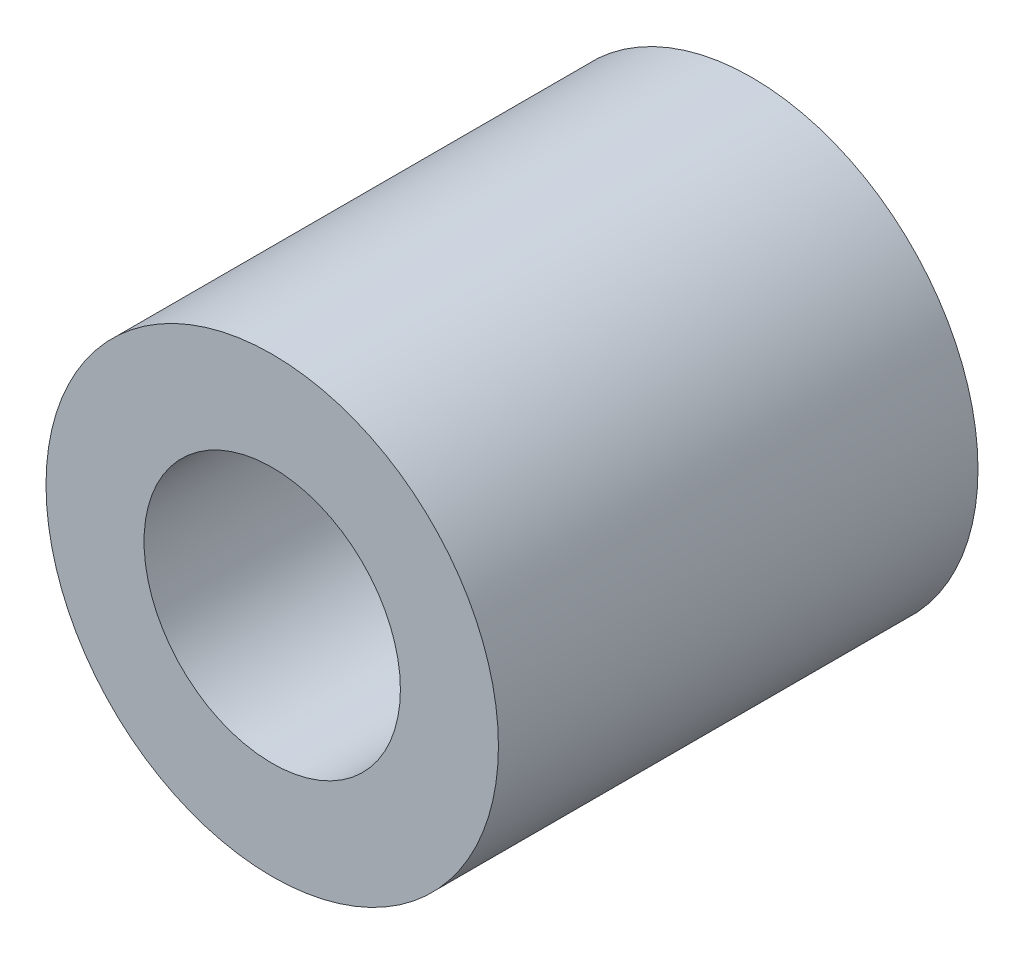
SolidWorks part; units mm, degrees
ref_plane "Front Plane" through (0, 0, 0) normal (0, 0, 1) x (1, 0, 0)
ref_plane "Top Plane" through (0, 0, 0) normal (0, 1, 0) x (1, 0, 0)
ref_plane "Right Plane" through (0, 0, 0) normal (1, 0, 0) x (0, 0, -1)
sketch "Sketch2" plane through (0, 0, 0) normal (0, 0, 1) x (1, 0, 0)
  circle A0 centre (0, 0) radius 4.25
  circle A1 centre (0, 0) radius 7.5
  dimension "D1" = 8.5
  dimension "D2" = 15
extrude "Boss-Extrude1" add sketch "Sketch2" along normal blind 15.9
